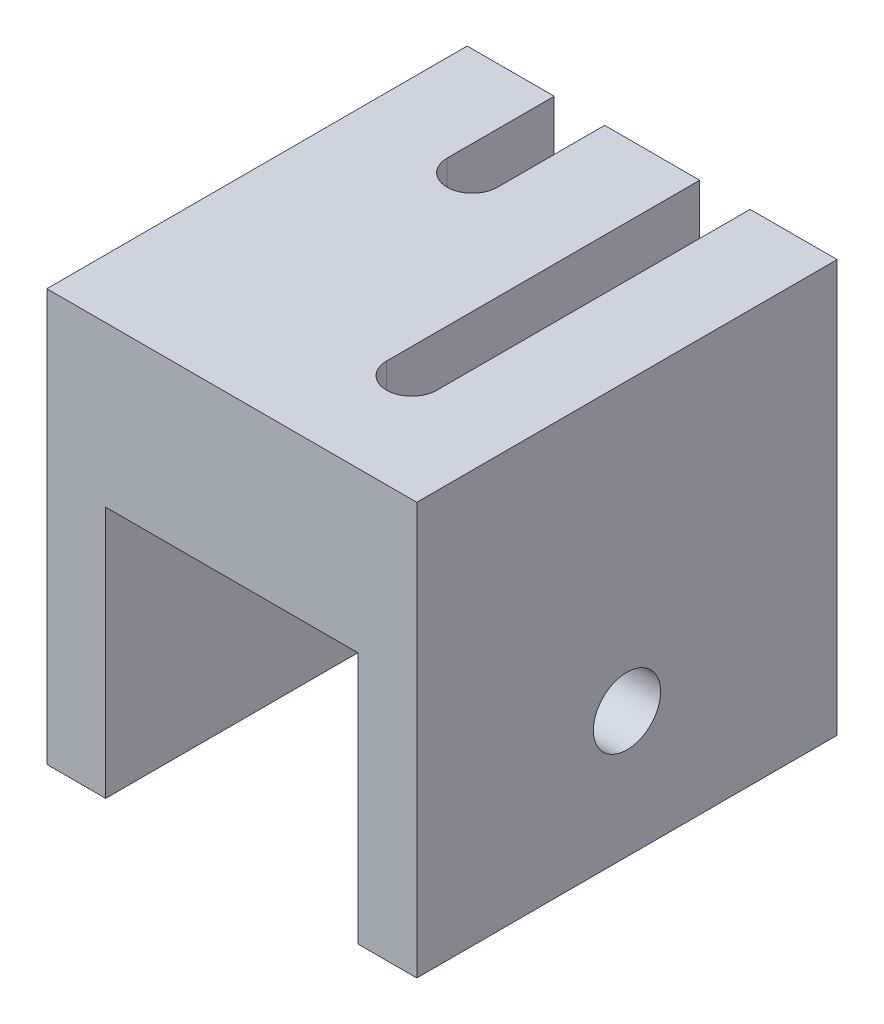
SolidWorks part; units mm, degrees
ref_plane "Front Plane" through (0, 0, 0) normal (0, 0, 1) x (1, 0, 0)
ref_plane "Top Plane" through (0, 0, 0) normal (0, 1, 0) x (1, 0, 0)
ref_plane "Right Plane" through (0, 0, 0) normal (1, 0, 0) x (0, 0, -1)
sketch "Sketch1" plane through (0, 0, 0) normal (0, 0, 1) x (1, 0, 0)
  line L0 (-22, -15) -> (-22, 22)
  line L5 (-15, 15) -> (15, -15) construction
  line L6 (-15, -15) -> (15, 15) construction
  line L11 (-22, 22) -> (22, 22)
  line L12 (22, -15) -> (22, 22)
  line L13 (-15, -15) -> (15, -15)
  line L14 (-15, -15) -> (-15, 15)
  line L15 (-15, 15) -> (15, 15)
  line L16 (15, -15) -> (15, 15)
  line L17 (-15, -15) -> (15, 15) construction
  line L18 (-15, 15) -> (15, -15) construction
  line L19 (-22, -15) -> (-15, -15)
  line L20 (15, -15) -> (22, -15)
  line L22 (-15, -15) -> (-22, -15)
  line L23 (-15, -15) -> (-15, 22)
  line L24 (-15, 22) -> (-22, 22)
  line L25 (-22, -15) -> (-22, 22)
  line L26 (-15, 22) -> (22, 22)
  line L27 (-15, 22) -> (-15, 15)
  line L28 (-15, 15) -> (22, 15)
  line L29 (22, 22) -> (22, 15)
  line L30 (22, -15) -> (15, -15)
  line L31 (22, -15) -> (22, 15)
  line L32 (22, 15) -> (15, 15)
  line L33 (15, -15) -> (15, 15)
  point P0 (0, 0)
  point P6 (0, 29.5014)
  point P11 (0, 0)
  dimension "D1" = 30
  dimension "D2" = 7
  dimension "D3" = 30
extrude "Boss-Extrude1" add sketch "Sketch1" along normal blind 50 contours L15 L28 L12 L11 L23 | L28 L16 L20 L12
sketch "Sketch3" plane through (0, 22, 0) normal (0, 1, 0) x (1, 0, 0)
  line L0 (0, 0) -> (0, -50) construction
  line L2 (-22, 0) -> (22, 0) construction
  line L5 (-22, -50) -> (22, -50) construction
  line L6 (0, -25) -> (-22, -25) construction
  line L7 (-22, -50) -> (-22, 0) construction
  line L8 (0, -25) -> (-8.6502, -12.7455) construction
  line L9 (0, -25) -> (8.6502, -37.2545) construction
  line L16 (-13.6502, -12.7455) -> (-13.6502, 0)
  line L17 (-3.6502, -12.7455) -> (-3.6502, 0)
  line L18 (3.6502, -37.2545) -> (3.6502, 0)
  line L19 (13.6502, -37.2545) -> (13.6502, 0)
  circle A2 centre (-8.6502, -12.7455) radius 5
  circle A3 centre (8.6502, -37.2545) radius 5
  dimension "D1" = 10
  dimension "D2" = 10
extrude "Boss-Extrude2" add sketch "Sketch3" along normal blind 6
sketch "Sketch4" plane through (0, 28, 0) normal (0, 1, 0) x (1, 0, 0)
  line L0 (5.6502, -37.2545) -> (5.6502, 0)
  line L1 (3.6502, 0) -> (13.6502, 0) construction
  line L2 (11.6502, -37.2545) -> (11.6502, 0)
  line L3 (-11.6502, -12.7455) -> (-11.6502, 0)
  line L4 (-13.6502, 0) -> (-3.6502, 0) construction
  line L5 (-5.6502, -12.7455) -> (-5.6502, 0)
  line L6 (-11.6502, 0) -> (-13.6502, 0)
  line L7 (-13.6502, 0) -> (-13.6502, -12.7455)
  line L8 (-3.6502, -12.7455) -> (-3.6502, 0)
  line L9 (-3.6502, -12.7455) -> (-3.6502, 0) construction
  line L10 (-3.6502, 0) -> (-5.6502, 0)
  line L11 (13.6502, -37.2545) -> (13.6502, 0)
  line L12 (13.6502, 0) -> (11.6502, 0)
  line L13 (3.6502, -37.2545) -> (3.6502, 0)
  line L14 (3.6502, 0) -> (5.6502, 0)
  circle A0 centre (8.6502, -37.2545) radius 3
  circle A1 centre (-8.6502, -12.7455) radius 3
  arc A2 (-13.6502, -12.7455) -> (-3.6502, -12.7455) centre (-8.6502, -12.7455) ccw
  arc A3 (-13.6502, -12.7455) -> (-3.6502, -12.7455) centre (-8.6502, -12.7455) ccw construction
  arc A4 (13.6502, -37.2545) -> (3.6502, -37.2545) centre (8.6502, -37.2545) cw
  arc A5 (3.6502, -37.2545) -> (13.6502, -37.2545) centre (8.6502, -37.2545) ccw construction
  arc M1 (13.6502, -37.2545) -> (3.6502, -37.2545) centre (8.6502, -37.2545) cw
  line M2 (3.6502, -37.2545) -> (3.6502, 0)
  line M3 (3.6502, 0) -> (-3.6502, 0)
  line M4 (-3.6502, 0) -> (-3.6502, -12.7455)
  arc M5 (-3.6502, -12.7455) -> (-13.6502, -12.7455) centre (-8.6502, -12.7455) cw
  line M6 (-13.6502, -12.7455) -> (-13.6502, 0)
  line M7 (-13.6502, 0) -> (-22, 0)
  line M8 (-22, 0) -> (-22, -50)
  line M9 (-22, -50) -> (22, -50)
  line M10 (22, -50) -> (22, 0)
  line M11 (22, 0) -> (13.6502, 0)
  line M12 (13.6502, 0) -> (13.6502, -37.2545)
  dimension "D1" = 6
  dimension "D2" = 6
extrude "Boss-Extrude4" add sketch "Sketch4" along normal blind 6 contours A0 L0 L14 L12 L2 M2 M1 M12 | A1 L3 L6 L10 L5 M6 M5 M4 | M12 M1 M2 M3 M4 M5 M6 M7 M8 M9 M10 M11
sketch "Sketch5" plane through (-22, 0, 0) normal (-1, 0, 0) x (0, 0, 1)
  line L0 (25, -15) -> (25, -4) construction
  line L1 (50, -15) -> (0, -15) construction
  line L2 (25, -4) -> (25, 4) construction
  line L3 (0, -4) -> (50, -4)
  line L4 (50, -15) -> (50, 34) construction
  line L5 (0, 4) -> (50, 4)
  line L6 (29, 0) -> (50, 0) construction
  circle A0 centre (25, 0) radius 4
  point P10 (25, -4)
  point P13 (25, 4)
  dimension "D1" = 11
  dimension "D2" = 8
extrude "Cut-Extrude1" cut sketch "Sketch5" against normal blind 59 contours A0 L5
